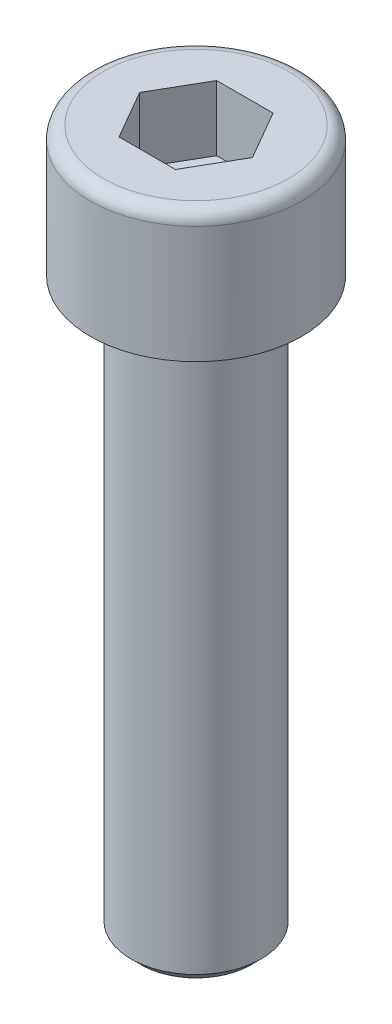
SolidWorks part; units mm, degrees
ref_plane "Front Plane" through (0, 0, 0) normal (0, 0, 1) x (1, 0, 0)
ref_plane "Top Plane" through (0, 0, 0) normal (0, 1, 0) x (1, 0, 0)
ref_plane "Right Plane" through (0, 0, 0) normal (1, 0, 0) x (0, 0, -1)
sketch "Sketch1" plane through (0, 0, 0) normal (0, 0, 1) x (1, 0, 0)
  line L0 (0, 0) -> (6.5, 0)
  line L1 (6.5, 0) -> (6.5, -8)
  line L2 (6.5, -8) -> (4, -8)
  line L3 (4, -8) -> (4, -43)
  line L4 (4, -43) -> (0, -43)
  line L5 (0, -43) -> (0, 0)
  line L6 (0, -48) -> (0, 5) construction
  dimension "D1" = 5
  dimension "D2" = 5
  dimension "H" = 8
  dimension "L" = 35
  dimension "D" = 8
  dimension "A" = 13
revolve "Revolve1" add sketch "Sketch1" angle 360 about L6
sketch "Sketch2" plane through (0, 0, 0) normal (0, 1, 0) x (1, 0, 0)
  line L7 (3.4641, 0) -> (1.7321, 3)
  line L8 (1.7321, 3) -> (-1.7321, 3)
  line L9 (-1.7321, 3) -> (-3.4641, 0)
  line L10 (-3.4641, 0) -> (-1.7321, -3)
  line L11 (-1.7321, -3) -> (1.7321, -3)
  line L12 (1.7321, -3) -> (3.4641, 0)
  circle A0 centre (0, 0) radius 3 construction
  dimension "D1" = 6
extrude "Cut-Extrude1" cut sketch "Sketch2" against normal blind 4
fillet "Fillet3" radius 0.8 1 edges at (0, 0, -6.5)
chamfer "Chamfer1" distance 0.625 angle 45 1 edges at (0, -43, -4)
cosmetic thread "Cosmetic Thread1" parameters "D1"=25, "D2"=6.619
ref_plane "ThreadStop" through (0, -11.75, 0) normal (0, -1, 0) x (-1, 0, 0)
fillet "Fillet4" [suppressed] radius 0.25
